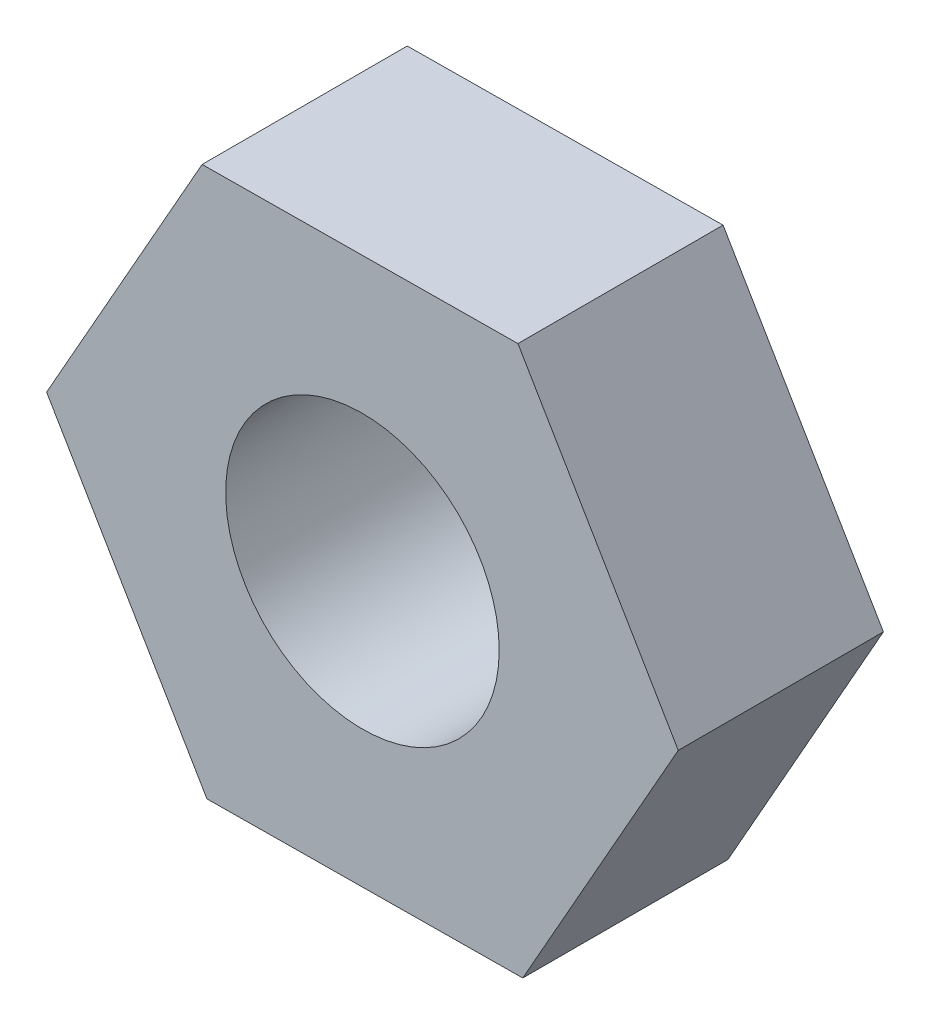
SolidWorks part; units mm, degrees
ref_plane "前视基准面" through (0, 0, 0) normal (0, 0, 1) x (1, 0, 0)
ref_plane "上视基准面" through (0, 0, 0) normal (0, 1, 0) x (1, 0, 0)
ref_plane "右视基准面" through (0, 0, 0) normal (1, 0, 0) x (0, 0, -1)
sketch "草图1" plane through (0, 0, 0) normal (0, 0, 1) x (1, 0, 0)
  line L1 (1.1723, -1.9898) -> (2.3093, 0.0203)
  line L2 (2.3093, 0.0203) -> (1.1371, 2.0101)
  line L3 (1.1371, 2.0101) -> (-1.1723, 1.9898)
  line L4 (-1.1723, 1.9898) -> (-2.3093, -0.0203)
  line L5 (-2.3093, -0.0203) -> (-1.1371, -2.0101)
  line L6 (-1.1371, -2.0101) -> (1.1723, -1.9898)
  circle A0 centre (0, 0) radius 2 construction
  circle A1 centre (0, 0) radius 1
extrude "凸台-拉伸1" add sketch "草图1" along normal blind 1.5
